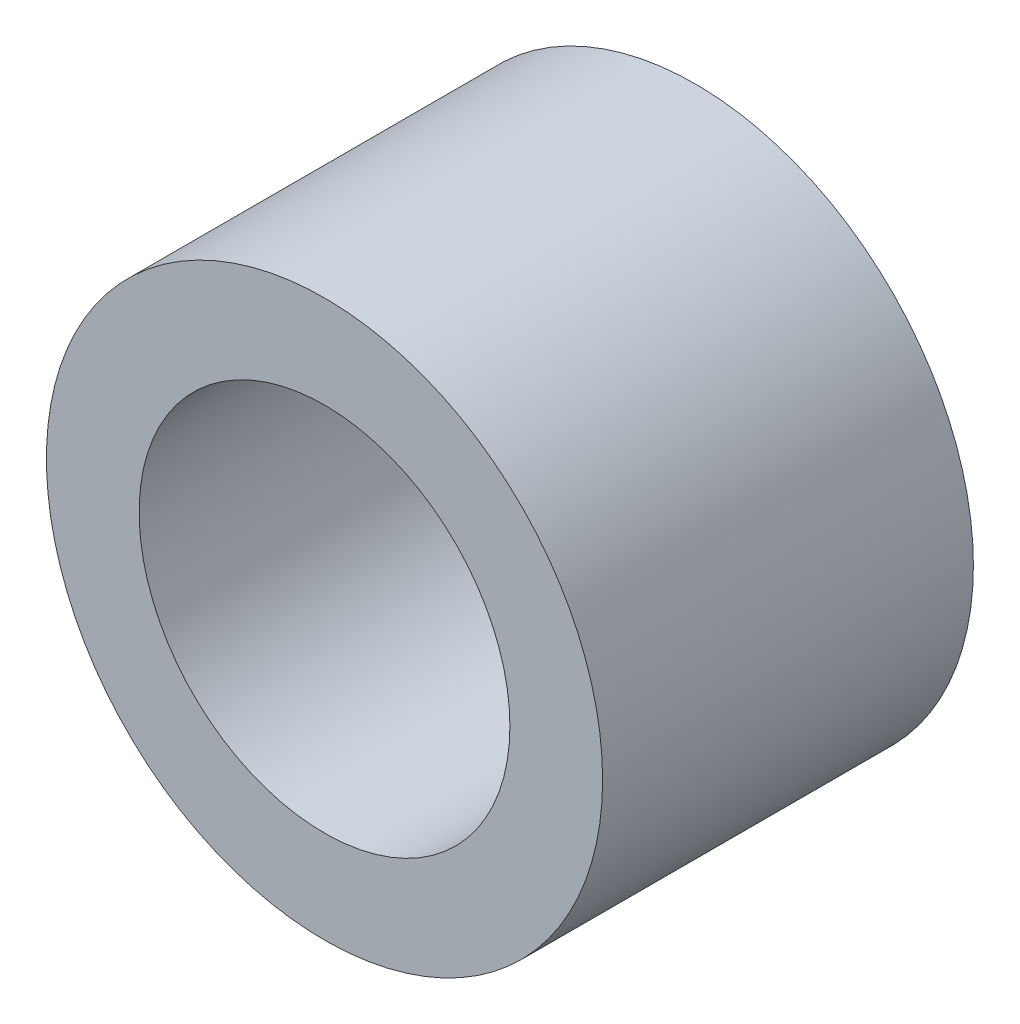
SolidWorks part; units mm, degrees
ref_plane "Front Plane" through (0, 0, 0) normal (0, 0, 1) x (1, 0, 0)
ref_plane "Top Plane" through (0, 0, 0) normal (0, 1, 0) x (1, 0, 0)
ref_plane "Right Plane" through (0, 0, 0) normal (1, 0, 0) x (0, 0, -1)
sketch "Sketch1" plane through (0, 0, 0) normal (0, 0, 1) x (1, 0, 0)
  circle A0 centre (0, 0) radius 9.525
  circle A1 centre (0, 0) radius 6.35
  dimension "D1" = 19.05
  dimension "D2" = 12.7
extrude "Boss-Extrude1" add sketch "Sketch1" along normal blind 12.7
